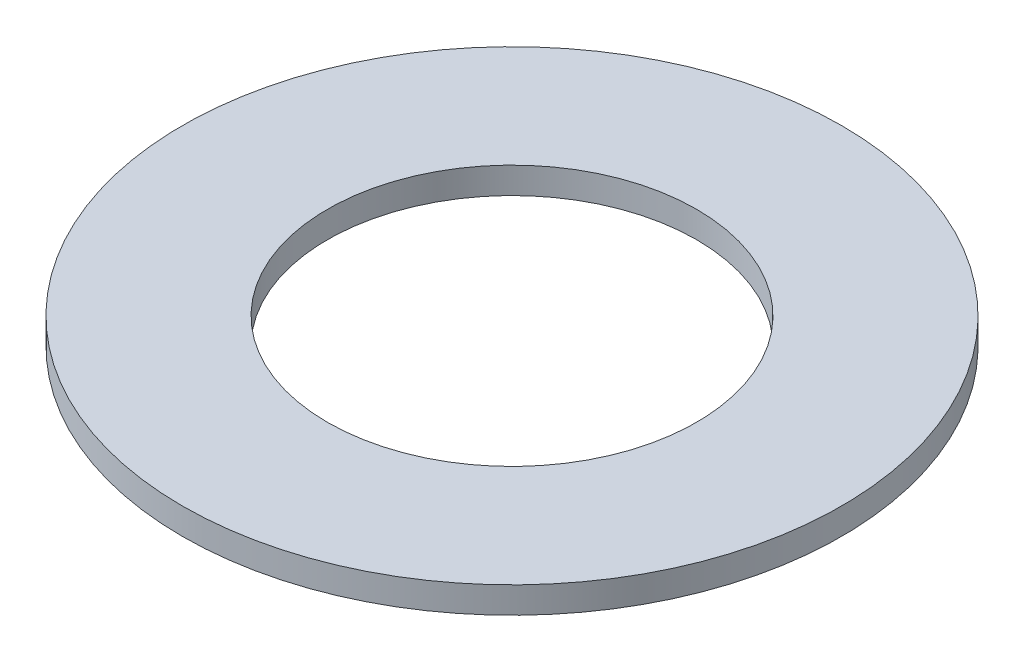
SolidWorks part; units mm, degrees
material "AISI 321 Annealed Stainless Steel (SS)"
ref_plane "Front Plane" through (0, 0, 0) normal (0, 0, 1) x (1, 0, 0)
ref_plane "Top Plane" through (0, 0, 0) normal (0, 1, 0) x (1, 0, 0)
ref_plane "Right Plane" through (0, 0, 0) normal (1, 0, 0) x (0, 0, -1)
sketch "Sketch1" plane through (0, 0, 0) normal (0, 1, 0) x (1, 0, 0)
  circle A0 centre (0, 0) radius 7
  circle A1 centre (0, 0) radius 12.5
  dimension "D1" = 14
  dimension "D2" = 25
extrude "Boss-Extrude1" add sketch "Sketch1" along normal mid plane 1
